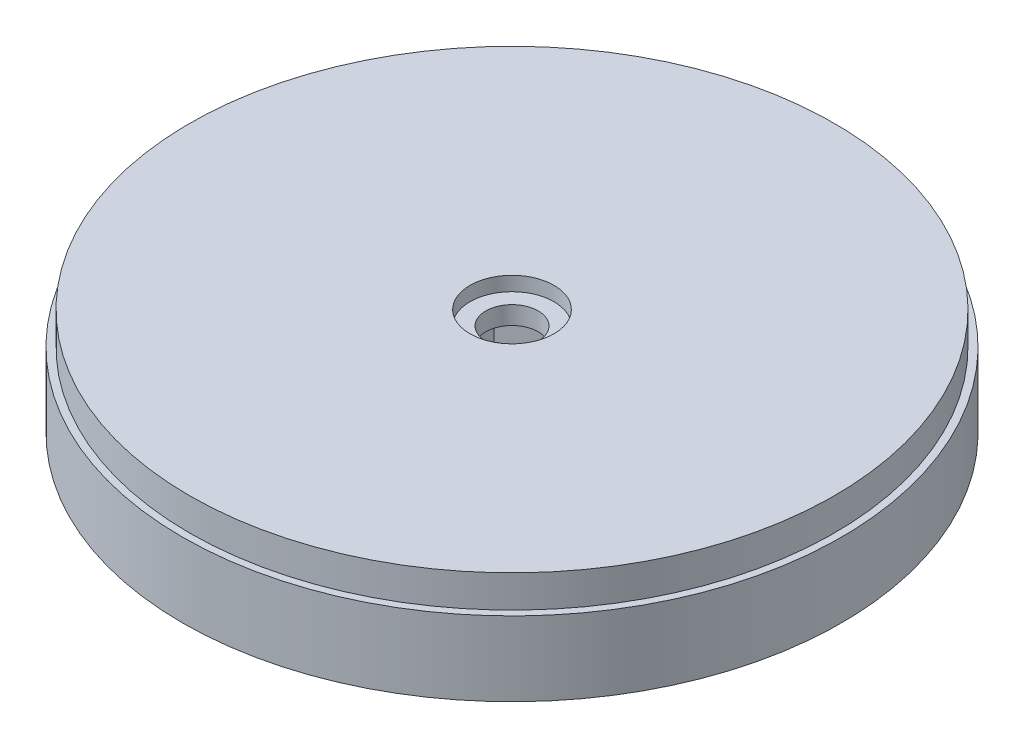
SolidWorks part; units mm, degrees
ref_plane "Front Plane" through (0, 0, 0) normal (0, 0, 1) x (1, 0, 0)
ref_plane "Top Plane" through (0, 0, 0) normal (0, 1, 0) x (1, 0, 0)
ref_plane "Right Plane" through (0, 0, 0) normal (1, 0, 0) x (0, 0, -1)
sketch "Sketch1" plane through (0, 0, 0) normal (0, 1, 0) x (1, 0, 0)
  line L1 (0, 7.5056) -> (-6.5, 3.7528)
  line L2 (-6.5, 3.7528) -> (-6.5, -3.7528)
  line L3 (-6.5, -3.7528) -> (0, -7.5056)
  line L4 (0, -7.5056) -> (6.5, -3.7528)
  line L5 (6.5, -3.7528) -> (6.5, 3.7528)
  line L6 (6.5, 3.7528) -> (0, 7.5056)
  circle A0 centre (0, 0) radius 51
  circle A1 centre (0, 0) radius 6.5 construction
  dimension "D1" = 102
  dimension "D2" = 13
extrude "Boss-Extrude1" add sketch "Sketch1" along normal blind 11.5
sketch "Sketch2" plane through (0, 11.5, 0) normal (0, 1, 0) x (1, 0, 0)
  circle A0 centre (0, 0) radius 4.05
  circle A1 centre (0, 0) radius 49.9
  circle A2 centre (0, 0) radius 51 construction
  dimension "D1" = 8.1
  dimension "D2" = 1.1
extrude "Boss-Extrude2" add sketch "Sketch2" along normal blind 5
sketch "Sketch3" plane through (0, 0, 0) normal (0, -1, 0) x (1, 0, 0)
  circle A0 centre (0, 0) radius 8
  dimension "D1" = 16
extrude "Cut-Extrude1" cut sketch "Sketch3" against normal blind 7
sketch "Sketch4" plane through (0, 16.5, 0) normal (0, 1, 0) x (1, 0, 0)
  circle A0 centre (0, 0) radius 6.5
  dimension "D1" = 13
extrude "Cut-Extrude2" cut sketch "Sketch4" against normal blind 2.2
